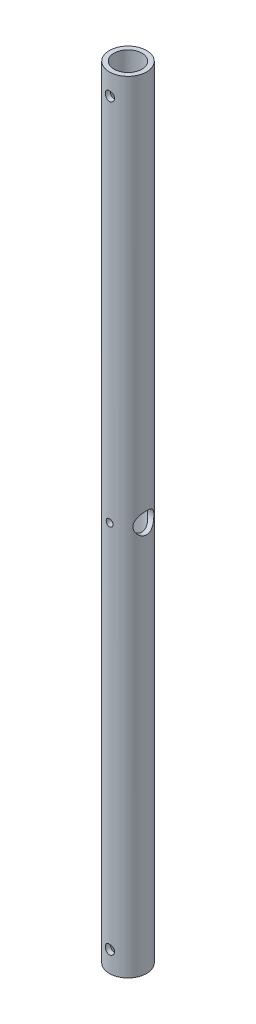
SolidWorks part; units mm, degrees
material "Aluminium"
ref_plane "Front Plane" through (0, 0, 0) normal (0, 0, 1) x (1, 0, 0)
ref_plane "Top Plane" through (0, 0, 0) normal (0, 1, 0) x (1, 0, 0)
ref_plane "Right Plane" through (0, 0, 0) normal (1, 0, 0) x (0, 0, -1)
sketch "Sketch1" plane through (0, 0, 0) normal (0, 1, 0) x (1, 0, 0)
  circle A0 centre (0, 0) radius 8
  circle A1 centre (0, 0) radius 6
  dimension "D1" = 2
  dimension "D2" = 16
extrude "Boss-Extrude1" add sketch "Sketch1" along normal mid plane 336
sketch "Sketch2" plane through (0, 0, 0) normal (1, 0, 0) x (0, 0, -1)
  circle A0 centre (0, 0) radius 4.5
  dimension "D1" = 9
extrude "Cut-Extrude1" cut sketch "Sketch2" against normal through all both and the other way through all
sketch "Sketch3" plane through (0, 0, 0) normal (0, 0, 1) x (1, 0, 0)
  circle A0 centre (0, 0) radius 1.5
  dimension "D1" = 3
extrude "Cut-Extrude2" cut sketch "Sketch3" against normal through all both and the other way through all
sketch "Sketch4" plane through (0, 0, 0) normal (0, 0, 1) x (1, 0, 0)
  line L0 (0, -159) -> (0, -168) construction
  line L1 (-8, -168) -> (8, -168) construction
  line L2 (0, 168) -> (0, 159) construction
  line L3 (6, 168) -> (-6, 168) construction
  circle A0 centre (0, 159) radius 2
  circle A1 centre (0, -159) radius 2
  dimension "D2" = 4
  dimension "D1" = 9
extrude "Cut-Extrude3" cut sketch "Sketch4" against normal through all both and the other way through all
